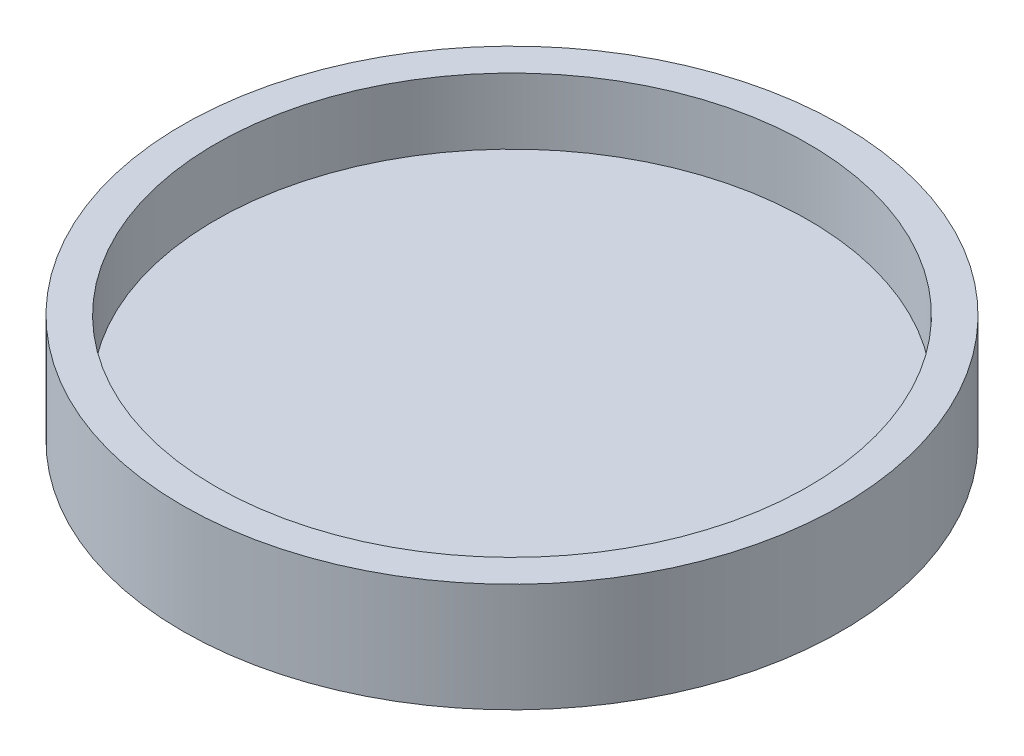
SolidWorks part; units mm, degrees
ref_plane "正面" through (0, 0, 0) normal (0, 0, 1) x (1, 0, 0)
ref_plane "平面" through (0, 0, 0) normal (0, 1, 0) x (1, 0, 0)
ref_plane "右側面" through (0, 0, 0) normal (1, 0, 0) x (0, 0, -1)
sketch "ｽｹｯﾁ1" plane through (0, 0, 0) normal (0, 1, 0) x (1, 0, 0)
  circle A0 centre (0, 0) radius 10
  dimension "D1" = 20
extrude "ﾎﾞｽ - 押し出し1" add sketch "ｽｹｯﾁ1" along normal blind 3.3
sketch "ｽｹｯﾁ2" plane through (0, 3.3, 0) normal (0, 1, 0) x (1, 0, 0)
  circle A0 centre (0, 0) radius 9
  dimension "D1" = 18
extrude "ｶｯﾄ - 押し出し1" cut sketch "ｽｹｯﾁ2" against normal blind 2
sketch "ｽｹｯﾁ3" plane through (0, 0, 0) normal (0, -1, 0) x (1, 0, 0)
  circle A0 centre (0, 0) radius 2.5
  dimension "D1" = 5
extrude "ｶｯﾄ - 押し出し2" cut sketch "ｽｹｯﾁ3" against normal blind 0.8
equation "\"G1モジュール\" = 1"
equation "\"G１歯数\"= 16"
equation "\"G１圧力角\"= 20"
equation "\"G1歯幅\" = 1.5"
equation "\"G2モジュール\" = 1"
equation "\"G2歯数\"= 16"
equation "\"G2圧力角\"= 20"
equation "\"G2歯幅\" = 1.5"
equation "\"G3モジュール\"= 1"
equation "\"G3歯数\"= 16"
equation "\"G3圧力角\"= 20"
equation "\"G3歯幅\"= 1.5"
